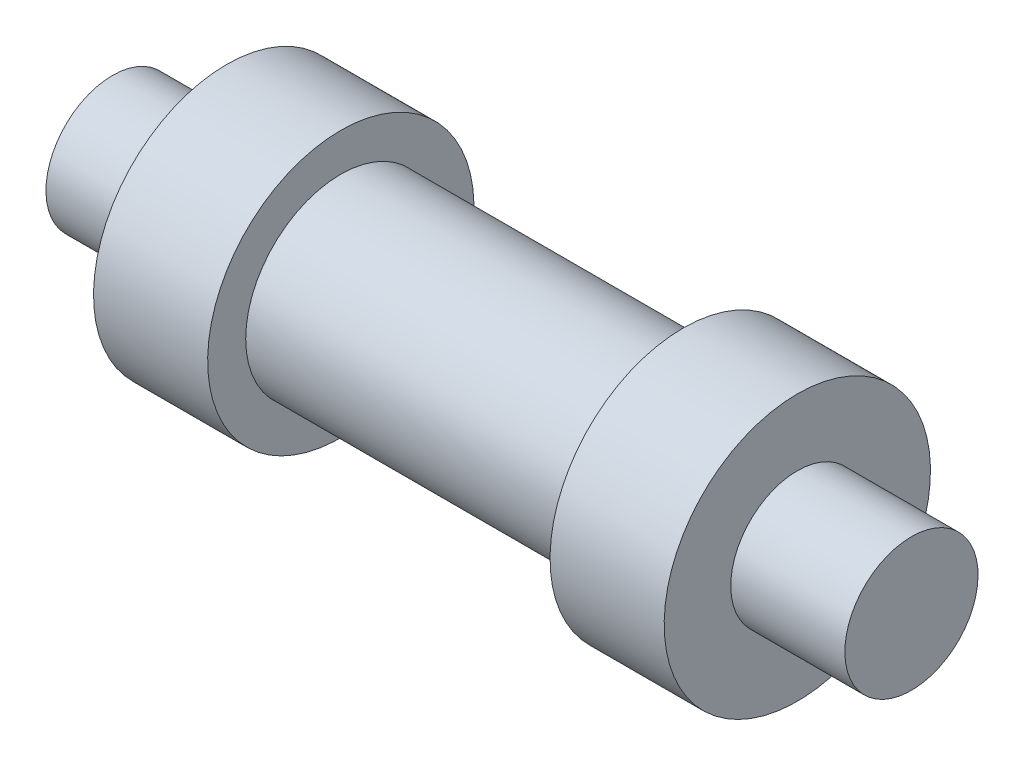
SolidWorks part; units mm, degrees
ref_plane "Front Plane" through (0, 0, 0) normal (0, 0, 1) x (1, 0, 0)
ref_plane "Top Plane" through (0, 0, 0) normal (0, 1, 0) x (1, 0, 0)
ref_plane "Right Plane" through (0, 0, 0) normal (1, 0, 0) x (0, 0, -1)
sketch "Sketch1" plane through (0, 0, 0) normal (0, 0, 1) x (1, 0, 0)
  line L0 (0, 0) -> (0, 3.5)
  line L1 (0, 3.5) -> (6, 3.5)
  line L2 (6, 3.5) -> (6, 7)
  line L3 (6, 7) -> (12, 7)
  line L4 (12, 7) -> (12, 5)
  line L5 (12, 5) -> (30, 5)
  line L6 (30, 5) -> (30, 7)
  line L7 (30, 7) -> (36, 7)
  line L8 (36, 7) -> (36, 3.5)
  line L9 (36, 3.5) -> (42, 3.5)
  line L10 (42, 3.5) -> (42, 0)
  line L11 (42, 0) -> (0, 0)
  dimension "D1" = 6
  dimension "D2" = 6
  dimension "D3" = 18
  dimension "D4" = 6
  dimension "D5" = 6
  dimension "D6" = 7
  dimension "D7" = 3.5
  dimension "D8" = 5
  dimension "D9" = 3.5
  dimension "D10" = 7
revolve "Revolve1" add sketch "Sketch1" angle 360 about L11
